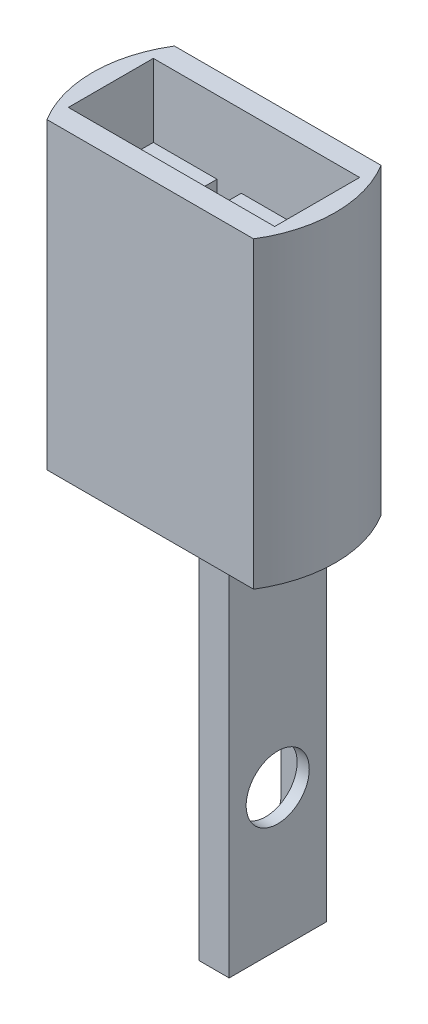
SolidWorks part; units mm, degrees
ref_plane "Front Plane" through (0, 0, 0) normal (0, 0, 1) x (1, 0, 0)
ref_plane "Top Plane" through (0, 0, 0) normal (0, 1, 0) x (1, 0, 0)
ref_plane "Right Plane" through (0, 0, 0) normal (1, 0, 0) x (0, 0, -1)
sketch "Sketch3" plane through (0, 0, 0) normal (0, 1, 0) x (1, 0, 0)
  circle A0 centre (0, 0) radius 10
  dimension "D1" = 20
extrude "Boss-Extrude1" add sketch "Sketch3" along normal blind 25
sketch "Sketch4" plane through (0, 0, 0) normal (0, -1, 0) x (-1, 0, 0)
  line L1 (-2.75, 4) -> (-5.25, 4)
  line L2 (-2.75, 4) -> (-2.75, -4)
  line L3 (-2.75, -4) -> (-5.25, -4)
  line L4 (-5.25, 4) -> (-5.25, -4)
  line L5 (-2.75, 4) -> (-5.25, -4) construction
  line L6 (-2.75, -4) -> (-5.25, 4) construction
  point P0 (-4, 0)
  dimension "D1" = 2.5
  dimension "D2" = 8
  dimension "D3" = 4
extrude "Boss-Extrude2" add sketch "Sketch4" along normal blind 30
sketch "Sketch5" plane through (5.25, 0, 0) normal (1, 0, 0) x (0, 0, -1)
  line L1 (4, 0) -> (-4, 0) construction
  circle A0 centre (0, -18.4) radius 2.6
  dimension "D1" = 5.2
  dimension "D2" = 18.4
extrude "Cut-Extrude1" cut sketch "Sketch5" against normal up to next
sketch "Sketch6" plane through (2.75, 0, 0) normal (-1, 0, 0) x (0, 0, 1)
  line L1 (-2.75, -28.9) -> (2.75, -28.9)
  line L2 (-2.75, -28.9) -> (-2.75, -7.9)
  line L3 (-2.75, -7.9) -> (2.75, -7.9)
  line L4 (2.75, -28.9) -> (2.75, -7.9)
  line L5 (-2.75, -28.9) -> (2.75, -7.9) construction
  line L6 (-2.75, -7.9) -> (2.75, -28.9) construction
  point P0 (0, -18.4)
  dimension "D1" = 21
  dimension "D2" = 5.5
extrude "Cut-Extrude2" cut sketch "Sketch6" against normal blind 1.5
sketch "Sketch7" plane through (0, 25, 0) normal (0, 1, 0) x (1, 0, 0)
  line L0 (-10, 0) -> (10, 0) construction
  line L1 (-8.5, -3.5) -> (8.5, -3.5)
  line L2 (-8.5, -3.5) -> (-8.5, 3.5)
  line L3 (-8.5, 3.5) -> (8.5, 3.5)
  line L4 (8.5, -3.5) -> (8.5, 3.5)
  circle A0 centre (0, 0) radius 10 construction
  point P4 (-8.5, 0)
  dimension "D1" = 7
  dimension "D2" = 17
  dimension "D3" = 1.5
extrude "Cut-Extrude3" cut sketch "Sketch7" against normal blind 6
sketch "Sketch8" plane through (0, 19, 0) normal (0, 1, 0) x (1, 0, 0)
  line L0 (8.5, 0) -> (-1.25, 0) construction
  line L1 (8.5, -3.5) -> (8.5, 3.5) construction
  line L2 (8.5, 3.5) -> (-8.5, 3.5) construction
  line L3 (-1.25, 3.5) -> (-3.25, 3.5)
  line L4 (-1.25, 3.5) -> (-1.25, -3.5)
  line L5 (-1.25, -3.5) -> (-3.25, -3.5)
  line L6 (-3.25, 3.5) -> (-3.25, -3.5)
  line L7 (-8.5, 3.5) -> (-8.5, -3.5) construction
  dimension "D1" = 9.75
  dimension "D2" = 2
extrude "Cut-Extrude4" cut sketch "Sketch8" against normal blind 4
sketch "Sketch9" plane through (4.25, 0, 0) normal (-1, 0, 0) x (0, 0, 1)
  line L0 (-2.75, -28.9) -> (-2.75, -21.9)
  line L1 (-2.75, -7.9) -> (-2.75, -28.9) construction
  line L2 (-2.75, -21.9) -> (-1.5, -28.9)
  line L3 (-2.75, -28.9) -> (2.75, -28.9) construction
  line L4 (-1.5, -28.9) -> (-2.75, -28.9)
  line L6 (-2.75, -18.4) -> (2.75, -18.4) construction
  line L7 (2.75, -28.9) -> (2.75, -7.9) construction
  line L8 (0, -28.9) -> (0, -7.9) construction
  line L9 (2.75, -7.9) -> (-2.75, -7.9) construction
  line L10 (1.5, -28.9) -> (2.75, -28.9)
  line L11 (2.75, -21.9) -> (1.5, -28.9)
  line L12 (2.75, -28.9) -> (2.75, -21.9)
  line L13 (2.75, -7.9) -> (2.75, -14.9)
  line L14 (2.75, -14.9) -> (1.5, -7.9)
  line L15 (1.5, -7.9) -> (2.75, -7.9)
  line L16 (-1.5, -7.9) -> (-2.75, -7.9)
  line L17 (-2.75, -14.9) -> (-1.5, -7.9)
  line L18 (-2.75, -7.9) -> (-2.75, -14.9)
  dimension "D1" = 1.25
  dimension "D2" = 7
extrude "Boss-Extrude3" add sketch "Sketch9" along normal up to surface (1.5 mm away) up to face at (2.75, -18.4, 0)
ref_plane "Plane1" through (4.25, -28.9, -1.5) normal (1, 0, 0) x (0, 0, -1)
sketch "Sketch11" plane through (0, 0, 0) normal (0, -1, 0) x (-1, 0, 0)
  line L0 (8.511, 5.25) -> (-8.511, 5.25)
  line L1 (0, 5.25) -> (0, 10) construction
  line L2 (-2.75, 4) -> (-5.25, 4) construction
  line L3 (0, 0) -> (-10, 0) construction
  line L4 (-10, 0) -> (10, 0) construction
  line L5 (8.511, -5.25) -> (-8.511, -5.25)
  arc A0 (-8.511, 5.25) -> (8.511, 5.25) centre (0, 0) cw
  circle A1 centre (0, 0) radius 10 construction
  arc A2 (-8.511, -5.25) -> (8.511, -5.25) centre (0, 0) ccw
  dimension "D1" = 1.25
extrude "Cut-Extrude5" cut sketch "Sketch11" against normal up to next
